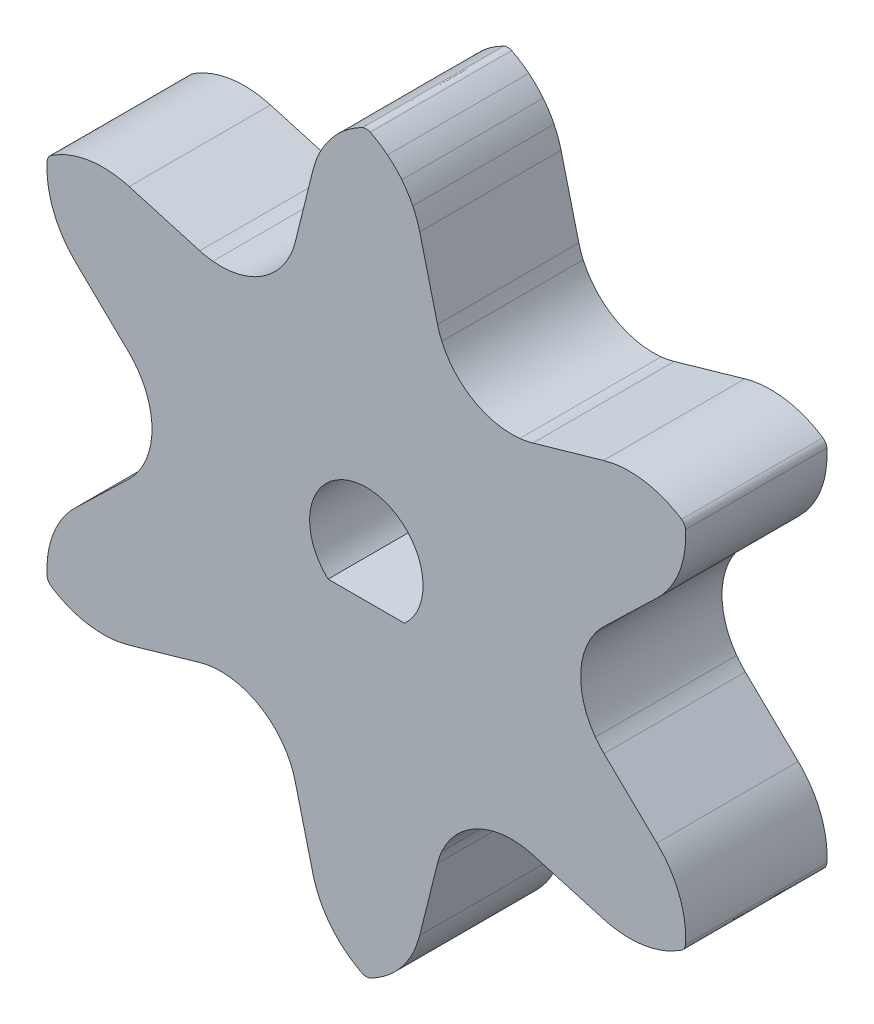
SolidWorks part; units mm, degrees
ref_plane "Front Plane" through (0, 0, 0) normal (0, 0, 1) x (1, 0, 0)
ref_plane "Top Plane" through (0, 0, 0) normal (0, 1, 0) x (1, 0, 0)
ref_plane "Right Plane" through (0, 0, 0) normal (1, 0, 0) x (0, 0, -1)
sketch "Sketch1" plane through (0, 0, 0) normal (0, 0, 1) x (1, 0, 0)
  arc B0 (-8.9081, -12.6618) -> (-7.243, -14.7357) centre (-5.8274, -11.8937) ccw
  line B1 (-8.4226, -3.8706) -> (-5.7958, -3.8706)
  arc B2 (-5.7958, -3.8706) -> (-8.4226, -3.8706) centre (-7.1092, -2.3956) ccw
  arc B3 (-17.8629, 3.6586) -> (-16.8994, 1.1795) centre (-14.6939, 3.4635) ccw
  line B4 (-5.3103, -12.6618) -> (-4.7111, -10.2584)
  line B5 (-9.5073, -10.2584) -> (-8.9081, -12.6618)
  line B6 (2.681, -5.9708) -> (0.8992, -4.2502)
  line B7 (-1.4989, -8.4039) -> (0.8821, -9.0866)
  line B8 (0.8821, 4.2953) -> (-1.4989, 3.6126)
  line B9 (0.8992, -0.5411) -> (2.681, 1.1795)
  line B10 (-8.9081, 7.8705) -> (-9.5073, 5.4671)
  line B11 (-4.7111, 5.4671) -> (-5.3103, 7.8705)
  line B12 (-16.8994, 1.1795) -> (-15.1176, -0.5411)
  line B13 (-12.7195, 3.6126) -> (-15.1005, 4.2953)
  line B14 (-15.1005, -9.0866) -> (-12.7195, -8.4039)
  line B15 (-15.1176, -4.2502) -> (-16.8994, -5.9708)
  arc B16 (-9.6527, -9.8356) -> (-12.2807, -8.3184) centre (-12.0089, -10.8821) ccw
  arc B17 (-4.5657, -9.8356) -> (-4.7111, -10.2584) centre (-2.2095, -10.8821) ccw
  arc B18 (-6.9755, -14.7357) -> (-5.3103, -12.6618) centre (-8.391, -11.8937) ccw
  arc B19 (-7.243, -14.7357) -> (-6.9755, -14.7357) centre (-7.1092, -14.4671) ccw
  arc B20 (-9.5073, -10.2584) -> (-9.6527, -9.8356) centre (-12.0089, -10.8821) ccw
  arc B21 (-1.9377, -8.3184) -> (-4.5657, -9.8356) centre (-2.2095, -10.8821) ccw
  arc B22 (0.6058, -3.9129) -> (0.8992, -4.2502) centre (2.6901, -2.3956) ccw
  arc B23 (3.6445, -8.4498) -> (2.681, -5.9708) centre (0.4755, -8.2547) ccw
  arc B24 (3.5107, -8.6815) -> (3.6445, -8.4498) centre (3.345, -8.4314) ccw
  arc B25 (0.8821, -9.0866) -> (3.5107, -8.6815) centre (1.7572, -6.0346) ccw
  arc B26 (-1.4989, -8.4039) -> (-1.9377, -8.3184) centre (-2.2095, -10.8821) ccw
  arc B27 (0.6058, -0.8784) -> (0.6058, -3.9129) centre (2.6901, -2.3956) ccw
  arc B28 (-1.9377, 3.5271) -> (-1.4989, 3.6126) centre (-2.2095, 6.0908) ccw
  arc B29 (3.5107, 3.8902) -> (0.8821, 4.2953) centre (1.7572, 1.2433) ccw
  arc B30 (3.6445, 3.6586) -> (3.5107, 3.8902) centre (3.345, 3.6401) ccw
  arc B31 (2.681, 1.1795) -> (3.6445, 3.6586) centre (0.4755, 3.4635) ccw
  arc B32 (0.8992, -0.5411) -> (0.6058, -0.8784) centre (2.6901, -2.3956) ccw
  arc B33 (-4.5657, 5.0444) -> (-1.9377, 3.5271) centre (-2.2095, 6.0908) ccw
  arc B34 (-9.6527, 5.0444) -> (-9.5073, 5.4671) centre (-12.0089, 6.0908) ccw
  arc B35 (-7.243, 9.9444) -> (-8.9081, 7.8705) centre (-5.8274, 7.1024) ccw
  arc B36 (-6.9755, 9.9444) -> (-7.243, 9.9444) centre (-7.1092, 9.6759) ccw
  arc B37 (-5.3103, 7.8705) -> (-6.9755, 9.9444) centre (-8.391, 7.1024) ccw
  arc B38 (-4.7111, 5.4671) -> (-4.5657, 5.0444) centre (-2.2095, 6.0908) ccw
  arc B39 (-12.2807, 3.5271) -> (-9.6527, 5.0444) centre (-12.0089, 6.0908) ccw
  arc B40 (-14.8242, -3.9129) -> (-14.8242, -0.8784) centre (-16.9085, -2.3956) ccw
  arc B41 (-14.8242, -0.8784) -> (-15.1176, -0.5411) centre (-16.9085, -2.3956) ccw
  arc B42 (-17.7291, 3.8902) -> (-17.8629, 3.6586) centre (-17.5634, 3.6401) ccw
  arc B43 (-15.1005, 4.2953) -> (-17.7291, 3.8902) centre (-15.9757, 1.2433) ccw
  arc B44 (-12.7195, 3.6126) -> (-12.2807, 3.5271) centre (-12.0089, 6.0908) ccw
  arc B45 (-12.2807, -8.3184) -> (-12.7195, -8.4039) centre (-12.0089, -10.8821) ccw
  arc B46 (-17.7291, -8.6815) -> (-15.1005, -9.0866) centre (-15.9757, -6.0346) ccw
  arc B47 (-17.8629, -8.4498) -> (-17.7291, -8.6815) centre (-17.5634, -8.4314) ccw
  arc B48 (-16.8994, -5.9708) -> (-17.8629, -8.4498) centre (-14.6939, -8.2547) ccw
  arc B49 (-15.1176, -4.2502) -> (-14.8242, -3.9129) centre (-16.9085, -2.3956) ccw
  arc B50 (0.6058, -0.8784) -> (0.6058, -3.9129) centre (2.6901, -2.3956) ccw
  arc B51 (-4.5657, 5.0444) -> (-1.9377, 3.5271) centre (-2.2095, 6.0908) ccw
  arc B52 (-9.6527, -9.8356) -> (-12.2807, -8.3184) centre (-12.0089, -10.8821) ccw
  arc B53 (-12.2807, 3.5271) -> (-9.6527, 5.0444) centre (-12.0089, 6.0908) ccw
  arc B54 (-1.9377, -8.3184) -> (-4.5657, -9.8356) centre (-2.2095, -10.8821) ccw
  arc B55 (-14.8242, -3.9129) -> (-14.8242, -0.8784) centre (-16.9085, -2.3956) ccw
  spline B56 degree 3 poles (0.8992, -4.2502) (0.7918, -4.1464) (0.6939, -4.034) (0.6058, -3.9129) knots 0 0 0 0 1 1 1 1
  spline B57 degree 3 poles (2.681, -5.9708) (2.0875, -5.3976) (1.4936, -4.8242) (0.8992, -4.2502) knots 0 0 0 0 1 1 1 1
  spline B58 degree 3 poles (3.6445, -8.4498) (3.6587, -8.2186) (3.6476, -7.9903) (3.5773, -7.5395) (3.5167, -7.3147) (3.3512, -6.8899) (3.2466, -6.6883) (2.9931, -6.3068) (2.846, -6.1301) (2.681, -5.9708) knots 0 0 0 0 0.25 0.25 0.5 0.5 0.75 0.75 1 1 1 1
  spline B59 degree 3 poles (3.6445, -8.4498) (3.6387, -8.5427) (3.5883, -8.6301) (3.5107, -8.6815) knots 0 0 0 0 1 1 1 1
  spline B60 degree 3 poles (0.8821, -9.0866) (1.1026, -9.1498) (1.3261, -9.1884) (1.7791, -9.2176) (2.011, -9.2076) (2.4617, -9.1388) (2.6818, -9.0807) (3.1112, -8.9156) (3.3175, -8.8095) (3.5107, -8.6815) knots 0 0 0 0 0.25 0.25 0.5 0.5 0.75 0.75 1 1 1 1
  spline B61 degree 3 poles (0.8821, -9.0866) (0.089, -8.8592) (-0.7046, -8.6316) (-1.4989, -8.4039) knots 0 0 0 0 1 1 1 1
  spline B62 degree 3 poles (-1.9377, -8.3184) (-1.7887, -8.3342) (-1.6425, -8.3627) (-1.4989, -8.4039) knots 0 0 0 0 1 1 1 1
  spline B63 degree 3 poles (-9.5073, 5.4671) (-9.5435, 5.3222) (-9.5919, 5.1813) (-9.6527, 5.0444) knots 0 0 0 0 1 1 1 1
  spline B64 degree 3 poles (-8.9081, 7.8705) (-9.1077, 7.0699) (-9.3074, 6.2689) (-9.5073, 5.4671) knots 0 0 0 0 1 1 1 1
  spline B65 degree 3 poles (-7.243, 9.9444) (-7.4504, 9.8411) (-7.6425, 9.7174) (-7.9977, 9.4311) (-8.1621, 9.2662) (-8.4472, 8.9105) (-8.5696, 8.7191) (-8.7732, 8.3088) (-8.8526, 8.0931) (-8.9081, 7.8705) knots 0 0 0 0 0.25 0.25 0.5 0.5 0.75 0.75 1 1 1 1
  spline B66 degree 3 poles (-7.243, 9.9444) (-7.1597, 9.9859) (-7.0587, 9.9859) (-6.9755, 9.9444) knots 0 0 0 0 1 1 1 1
  spline B67 degree 3 poles (-5.3103, 7.8705) (-5.3658, 8.0931) (-5.4442, 8.306) (-5.6453, 8.7128) (-5.77, 8.9087) (-6.0549, 9.2647) (-6.2153, 9.4262) (-6.5729, 9.7155) (-6.768, 9.8411) (-6.9755, 9.9444) knots 0 0 0 0 0.25 0.25 0.5 0.5 0.75 0.75 1 1 1 1
  spline B68 degree 3 poles (-5.3103, 7.8705) (-5.1107, 7.0699) (-4.911, 6.2689) (-4.7111, 5.4671) knots 0 0 0 0 1 1 1 1
  spline B69 degree 3 poles (-4.5657, 5.0444) (-4.6265, 5.1813) (-4.6749, 5.3222) (-4.7111, 5.4671) knots 0 0 0 0 1 1 1 1
  spline B70 degree 3 poles (-4.7111, -10.2584) (-4.6749, -10.1135) (-4.6265, -9.9725) (-4.5657, -9.8356) knots 0 0 0 0 1 1 1 1
  spline B71 degree 3 poles (-5.3103, -12.6618) (-5.1107, -11.8612) (-4.911, -11.0602) (-4.7111, -10.2584) knots 0 0 0 0 1 1 1 1
  spline B72 degree 3 poles (-6.9755, -14.7357) (-6.7681, -14.6324) (-6.5759, -14.5087) (-6.2207, -14.2223) (-6.0563, -14.0574) (-5.7712, -13.7018) (-5.6488, -13.5104) (-5.4452, -13.1001) (-5.3658, -12.8843) (-5.3103, -12.6618) knots 0 0 0 0 0.25 0.25 0.5 0.5 0.75 0.75 1 1 1 1
  spline B73 degree 3 poles (-6.9755, -14.7357) (-7.0587, -14.7771) (-7.1597, -14.7771) (-7.243, -14.7357) knots 0 0 0 0 1 1 1 1
  spline B74 degree 3 poles (-8.9081, -12.6618) (-8.8526, -12.8844) (-8.7742, -13.0972) (-8.5731, -13.5041) (-8.4485, -13.7) (-8.1635, -14.0559) (-8.0031, -14.2174) (-7.6455, -14.5067) (-7.4504, -14.6324) (-7.243, -14.7357) knots 0 0 0 0 0.25 0.25 0.5 0.5 0.75 0.75 1 1 1 1
  spline B75 degree 3 poles (-8.9081, -12.6618) (-9.1077, -11.8612) (-9.3074, -11.0602) (-9.5073, -10.2584) knots 0 0 0 0 1 1 1 1
  spline B76 degree 3 poles (-9.6527, -9.8356) (-9.5919, -9.9725) (-9.5435, -10.1135) (-9.5073, -10.2584) knots 0 0 0 0 1 1 1 1
  spline B77 degree 3 poles (-15.1176, -0.5411) (-15.0102, -0.6449) (-14.9124, -0.7572) (-14.8242, -0.8784) knots 0 0 0 0 1 1 1 1
  spline B78 degree 3 poles (-16.8994, 1.1795) (-16.3059, 0.6064) (-15.7121, 0.0329) (-15.1176, -0.5411) knots 0 0 0 0 1 1 1 1
  spline B79 degree 3 poles (-17.8629, 3.6586) (-17.8771, 3.4273) (-17.8661, 3.199) (-17.7957, 2.7482) (-17.7351, 2.5234) (-17.5696, 2.0987) (-17.465, 1.897) (-17.2116, 1.5155) (-17.0644, 1.3389) (-16.8994, 1.1795) knots 0 0 0 0 0.25 0.25 0.5 0.5 0.75 0.75 1 1 1 1
  spline B80 degree 3 poles (-17.8629, 3.6586) (-17.8572, 3.7514) (-17.8067, 3.8388) (-17.7291, 3.8902) knots 0 0 0 0 1 1 1 1
  spline B81 degree 3 poles (-15.1005, 4.2953) (-15.321, 4.3586) (-15.5446, 4.3971) (-15.9975, 4.4264) (-16.2295, 4.4164) (-16.6801, 4.3476) (-16.9002, 4.2894) (-17.3296, 4.1244) (-17.5359, 4.0182) (-17.7291, 3.8902) knots 0 0 0 0 0.25 0.25 0.5 0.5 0.75 0.75 1 1 1 1
  spline B82 degree 3 poles (-15.1005, 4.2953) (-14.3074, 4.0679) (-13.5138, 3.8404) (-12.7195, 3.6126) knots 0 0 0 0 1 1 1 1
  spline B83 degree 3 poles (-12.2807, 3.5271) (-12.4297, 3.5429) (-12.5759, 3.5714) (-12.7195, 3.6126) knots 0 0 0 0 1 1 1 1
  spline B84 degree 3 poles (-1.4989, 3.6126) (-1.6425, 3.5714) (-1.7887, 3.5429) (-1.9377, 3.5271) knots 0 0 0 0 1 1 1 1
  spline B85 degree 3 poles (0.8821, 4.2953) (0.089, 4.0679) (-0.7046, 3.8404) (-1.4989, 3.6126) knots 0 0 0 0 1 1 1 1
  spline B86 degree 3 poles (3.5107, 3.8902) (3.3176, 4.0182) (3.1143, 4.1227) (2.6888, 4.2872) (2.4638, 4.3471) (2.0132, 4.4162) (1.7863, 4.4265) (1.3291, 4.3977) (1.1026, 4.3586) (0.8821, 4.2953) knots 0 0 0 0 0.25 0.25 0.5 0.5 0.75 0.75 1 1 1 1
  spline B87 degree 3 poles (3.5107, 3.8902) (3.5883, 3.8388) (3.6387, 3.7514) (3.6445, 3.6586) knots 0 0 0 0 1 1 1 1
  spline B88 degree 3 poles (2.681, 1.1795) (2.846, 1.3389) (2.9912, 1.5132) (3.243, 1.8908) (3.3503, 2.0967) (3.5161, 2.5214) (3.5757, 2.7411) (3.6475, 3.1955) (3.6587, 3.4273) (3.6445, 3.6586) knots 0 0 0 0 0.25 0.25 0.5 0.5 0.75 0.75 1 1 1 1
  spline B89 degree 3 poles (0.8992, -0.5411) (1.4936, 0.0329) (2.0875, 0.6064) (2.681, 1.1795) knots 0 0 0 0 1 1 1 1
  spline B90 degree 3 poles (0.6058, -0.8784) (0.6939, -0.7572) (0.7918, -0.6449) (0.8992, -0.5411) knots 0 0 0 0 1 1 1 1
  spline B91 degree 3 poles (-15.1005, -9.0866) (-14.3074, -8.8592) (-13.5138, -8.6316) (-12.7195, -8.4039) knots 0 0 0 0 1 1 1 1
  spline B92 degree 3 poles (-17.7291, -8.6815) (-17.536, -8.8094) (-17.3328, -8.914) (-16.9072, -9.0784) (-16.6822, -9.1384) (-16.2316, -9.2075) (-16.0047, -9.2177) (-15.5476, -9.1889) (-15.321, -9.1498) (-15.1005, -9.0866) knots 0 0 0 0 0.25 0.25 0.5 0.5 0.75 0.75 1 1 1 1
  spline B93 degree 3 poles (-17.7291, -8.6815) (-17.8067, -8.6301) (-17.8572, -8.5427) (-17.8629, -8.4498) knots 0 0 0 0 1 1 1 1
  spline B94 degree 3 poles (-16.8994, -5.9708) (-17.0644, -6.1302) (-17.2096, -6.3045) (-17.4614, -6.6821) (-17.5687, -6.888) (-17.7345, -7.3127) (-17.7942, -7.5324) (-17.8659, -7.9867) (-17.8771, -8.2185) (-17.8629, -8.4498) knots 0 0 0 0 0.25 0.25 0.5 0.5 0.75 0.75 1 1 1 1
  spline B95 degree 3 poles (-15.1176, -4.2502) (-15.7121, -4.8242) (-16.3059, -5.3976) (-16.8994, -5.9708) knots 0 0 0 0 1 1 1 1
  spline B96 degree 3 poles (-12.7195, -8.4039) (-12.5759, -8.3627) (-12.4297, -8.3342) (-12.2807, -8.3184) knots 0 0 0 0 1 1 1 1
  spline B97 degree 3 poles (-14.8242, -3.9129) (-14.9124, -4.034) (-15.0102, -4.1464) (-15.1176, -4.2502) knots 0 0 0 0 1 1 1 1
sketch_block_instance "motorsprocket-1"
sketch_block "motorsprocket"
other "DetailItem3"
other "DetailItem4"
extrude "Boss-Extrude1" add sketch "Sketch1" along normal blind 4.7625 contours B40 B97 B15 B48 B93 B46 B14 B96 B16 B76 B5 B0 B74 B73 B18 B4 B70 B21 B62 B7 B25 B59 B23 B6 B56 B27 B90 B9 B31 B87 B29 B8 B84 B33 B69 B11 B37 B67 B66 B35 B10 B63 B39 B83 B13 B43 B80
ref_plane "Plane1" through (-5.7958, -3.8706, 4.7625) normal (1, 0, 0) x (0, 0, -1)
sketch "Sketch4" plane through (0, 0, 4.7625) normal (0, 0, 1) x (1, 0, 0)
  line L12 (-8.4226, -3.8706) -> (-5.7958, -3.8706) construction
  line L13 (-8.4226, -3.8706) -> (-5.7958, -3.8706)
  line L14 (-8.3982, -3.8071) -> (-5.8202, -3.8071)
  arc A24 (-5.7958, -3.8706) -> (-8.4226, -3.8706) centre (-7.1092, -2.3956) ccw construction
  arc A25 (-5.7958, -3.8706) -> (-8.4226, -3.8706) centre (-7.1092, -2.3956) ccw
  arc A26 (-5.8202, -3.8071) -> (-8.3982, -3.8071) centre (-7.1092, -2.3956) ccw
  dimension "D1" = 0.0635
extrude "Boss-Extrude2" add sketch "Sketch4" against normal blind 4.7625
